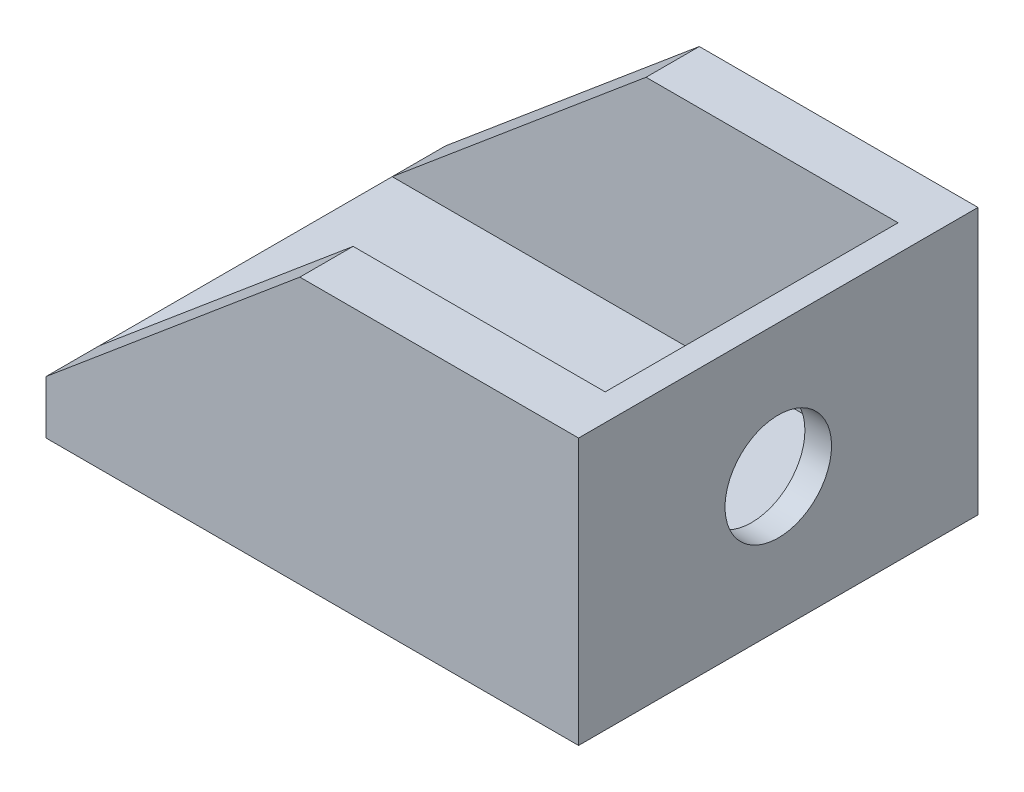
SolidWorks part; units mm, degrees
ref_plane "Front Plane" through (0, 0, 0) normal (0, 0, 1) x (1, 0, 0)
ref_plane "Top Plane" through (0, 0, 0) normal (0, 1, 0) x (1, 0, 0)
ref_plane "Right Plane" through (0, 0, 0) normal (1, 0, 0) x (0, 0, -1)
sketch "Sketch2" plane through (0, 0, 0) normal (0, 1, 0) x (1, 0, 0)
  line L1 (0, 0) -> (20, 0)
  line L2 (0, 0) -> (0, 13)
  line L3 (0, 13) -> (20, 13)
  line L4 (20, 0) -> (20, 13)
  dimension "D1" = 20
  dimension "D2" = 13
extrude "Boss-Extrude1" add sketch "Sketch2" along normal blind 2
sketch "Sketch3" plane through (0, 0, 0) normal (0, 0, 1) x (1, 0, 0)
  line L0 (20, 2) -> (20, 0) construction
  line L1 (0, 0) -> (20, 0)
  line L2 (0, 0) -> (0, 2)
  line L3 (9.534, 10) -> (20, 10)
  line L4 (20, 0) -> (20, 10)
  line L5 (0, 2) -> (9.534, 10)
  dimension "D1" = 10
  dimension "D2" = 140
extrude "Boss-Extrude2" add sketch "Sketch3" along normal blind 2
ref_plane "Plane1" through (0, 0, -5.5) normal (0, 0, 1) x (1, 0, 0)
mirror "Mirror1" about plane through (0, 0, -5.5) normal (0, 0, 1) of "Boss-Extrude1", "Boss-Extrude2"
sketch "Sketch4" plane through (20, 0, 0) normal (1, 0, 0) x (0, 0, -1)
  line L1 (0, 2) -> (11, 2)
  line L2 (0, 2) -> (0, 10)
  line L3 (0, 10) -> (11, 10)
  line L4 (11, 2) -> (11, 10)
extrude "Boss-Extrude3" add sketch "Sketch4" against normal blind 1
sketch "Sketch5" plane through (20, 0, 0) normal (1, 0, 0) x (0, 0, -1)
  line L0 (5.5, 10) -> (5.5, 0) construction
  line L1 (-2, 10) -> (13, 10) construction
  line L2 (5.5, 5.5) -> (5.5, -5.5) construction
  line L3 (-2, 0) -> (13, 0) construction
  circle A0 centre (5.5, 5) radius 2
  dimension "D1" = 4
  dimension "D2" = 5
extrude "Cut-Extrude1" cut sketch "Sketch5" against normal blind 6
